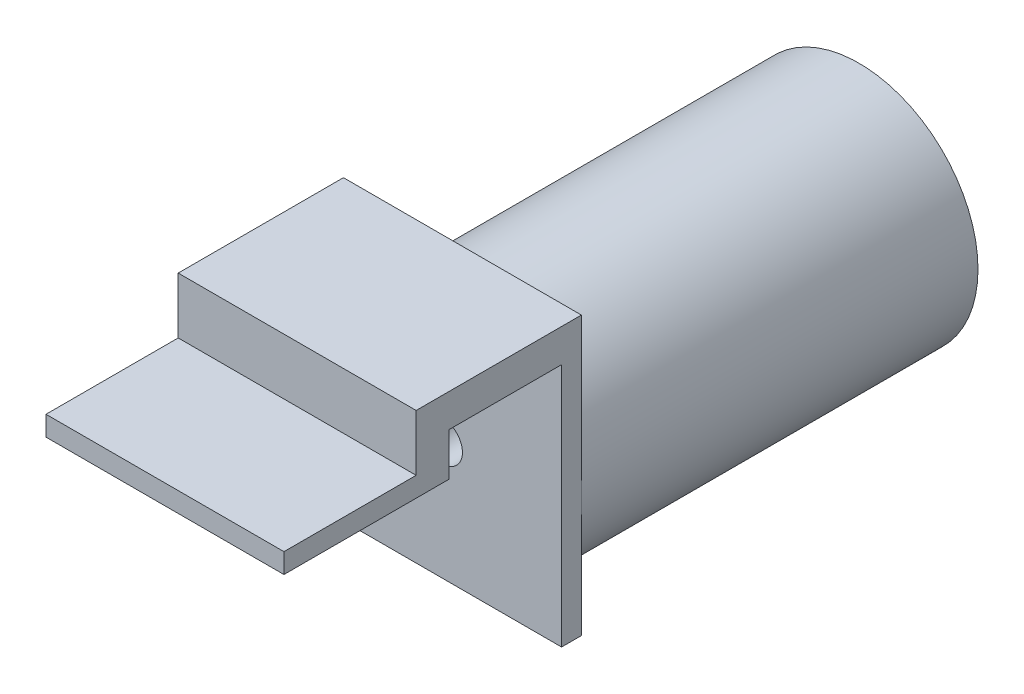
SolidWorks part; units mm, degrees
ref_plane "Front Plane" through (0, 0, 0) normal (0, 0, 1) x (1, 0, 0)
ref_plane "Top Plane" through (0, 0, 0) normal (0, 1, 0) x (1, 0, 0)
ref_plane "Right Plane" through (0, 0, 0) normal (1, 0, 0) x (0, 0, -1)
sketch "Sketch2" plane through (0, 0, 0) normal (0, 0, 1) x (1, 0, 0)
  circle A0 centre (0, 0) radius 18
extrude "Boss-Extrude1" add sketch "Sketch2" along normal blind 60
sketch "Sketch3" plane through (0, 0, 60) normal (0, 0, 1) x (1, 0, 0)
  circle A0 centre (0, 0) radius 3
  dimension "D1" = 0
sketch "Sketch4" plane through (0, 0, 60) normal (0, 0, 1) x (1, 0, 0)
  line L1 (-18, 24) -> (18, 24)
  line L2 (-18, 24) -> (-18, -18)
  line L3 (-18, -18) -> (18, -18)
  line L4 (18, 24) -> (18, -18)
  point P0 (0, 0)
  dimension "D1" = 36
  dimension "D2" = 42
  dimension "D3" = 18
extrude "Boss-Extrude2" add sketch "Sketch4" along normal blind 3
extrude "Cut-Extrude1" cut sketch "Sketch3" against normal blind 60 and the other way blind 3
sketch "Sketch6" plane through (0, 24, 0) normal (0, 1, 0) x (1, 0, 0)
  line L0 (-18, -63) -> (-18, -80)
  line L1 (-18, -80) -> (18, -80)
  line L2 (18, -80) -> (18, -63)
  line L3 (18, -63) -> (-18, -63)
  dimension "D1" = 17
extrude "Boss-Extrude3" add sketch "Sketch6" against normal blind 5
sketch "Sketch7" plane through (0, 0, 80) normal (0, 0, 1) x (1, 0, 0)
  line L1 (18, 19) -> (18, 12.5)
  line L2 (18, -18) -> (18, 19) construction
  line L3 (18, 12.5) -> (-18, 12.5)
  line L4 (-18, 19) -> (-18, -18) construction
  line L5 (-18, 12.5) -> (-18, 19)
  line L6 (-18, 24) -> (18, 24)
  line L7 (18, 24) -> (18, 19)
  line L8 (-18, 19) -> (-18, 24)
  dimension "D1" = 6.5
extrude "Boss-Extrude4" add sketch "Sketch7" along normal blind 5
sketch "Sketch8" plane through (0, 0, 85) normal (0, 0, 1) x (1, 0, 0)
  line L0 (-18, 12.5) -> (-18, 15.5)
  line L1 (-18, 24) -> (-18, 12.5) construction
  line L2 (-18, 15.5) -> (18, 15.5)
  line L3 (18, 12.5) -> (18, 24) construction
  line L4 (18, 15.5) -> (18, 12.5)
  line L5 (18, 12.5) -> (-18, 12.5)
  dimension "D1" = 3
extrude "Boss-Extrude5" add sketch "Sketch8" along normal blind 20
